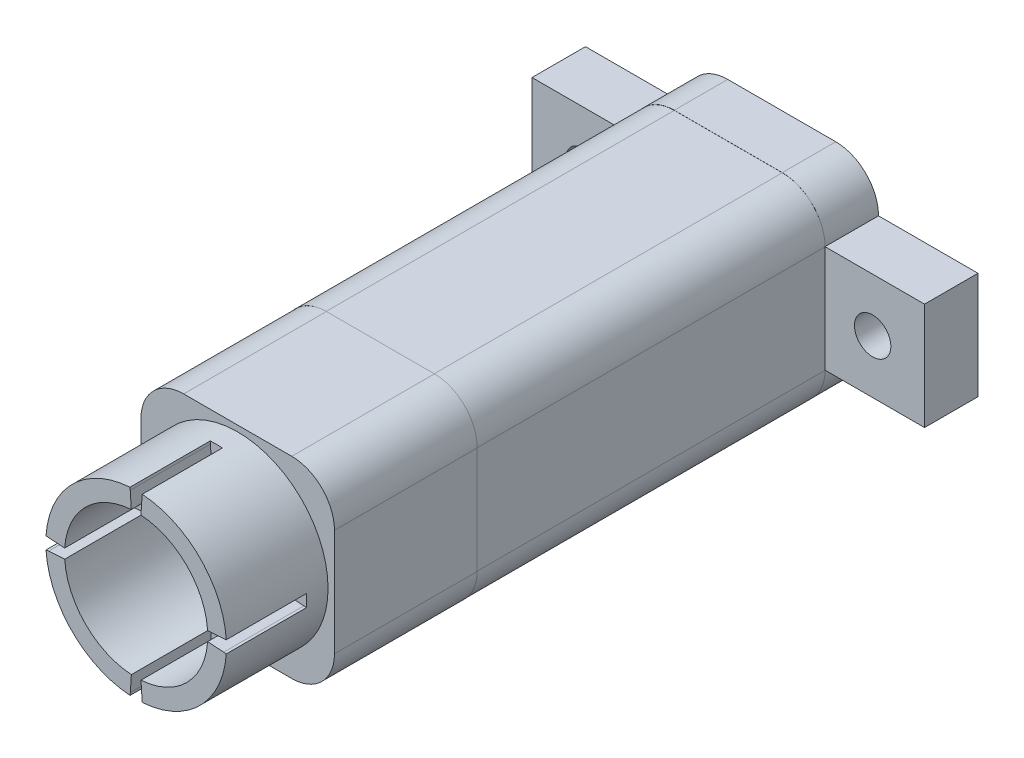
SolidWorks part; units mm, degrees
ref_plane "Front Plane" through (0, 0, 0) normal (0, 0, 1) x (1, 0, 0)
ref_plane "Top Plane" through (0, 0, 0) normal (0, 1, 0) x (1, 0, 0)
ref_plane "Right Plane" through (0, 0, 0) normal (1, 0, 0) x (0, 0, -1)
sketch "Sketch1" plane through (0, 0, 0) normal (0, 0, 1) x (1, 0, 0)
  line L12 (-5.05, 9.0001) -> (5.05, 9.0001)
  line L13 (-9.05, 5.0001) -> (-9.05, -5.0001)
  line L14 (-5.05, -9.0001) -> (5.05, -9.0001)
  line L15 (9.05, 5.0001) -> (9.05, -5.0001)
  line L16 (-9.05, 9.0001) -> (9.05, -9.0001) construction
  line L17 (-9.05, -9.0001) -> (9.05, 9.0001) construction
  arc A4 (-9.05, -5.0001) -> (-5.05, -9.0001) centre (-5.05, -5.0001) ccw
  arc A5 (5.05, -9.0001) -> (9.05, -5.0001) centre (5.05, -5.0001) ccw
  arc A6 (5.05, 9.0001) -> (9.05, 5.0001) centre (5.05, 5.0001) cw
  arc A7 (-5.05, 9.0001) -> (-9.05, 5.0001) centre (-5.05, 5.0001) ccw
  point P0 (0, 0)
  dimension "D2" = 4
  dimension "D1" = 9.05
extrude "Boss-Extrude1" add sketch "Sketch1" along normal blind 2
sketch "Sketch2" plane through (0, 0, 0) normal (0, 0, 1) x (1, 0, 0)
  line L0 (-5.05, 9.0001) -> (5.05, 9.0001)
  line L1 (-9.05, 5.0001) -> (-9.05, -5.0001)
  line L2 (-5.05, -9.0001) -> (5.05, -9.0001)
  line L3 (9.05, 5.0001) -> (9.05, -5.0001)
  line L4 (-9.05, 9.0001) -> (9.05, -9.0001) construction
  line L5 (-9.05, -9.0001) -> (9.05, 9.0001) construction
  arc A0 (-9.05, -5.0001) -> (-5.05, -9.0001) centre (-5.05, -5.0001) ccw
  arc A1 (5.05, -9.0001) -> (9.05, -5.0001) centre (5.05, -5.0001) ccw
  arc A2 (5.05, 9.0001) -> (9.05, 5.0001) centre (5.05, 5.0001) cw
  arc A3 (-5.05, 9.0001) -> (-9.05, 5.0001) centre (-5.05, 5.0001) ccw
  point P0 (0, 0)
  dimension "D2" = 4
  dimension "D1" = 9.05
extrude "Boss-Extrude2" add sketch "Sketch2" along normal blind 11.7499
sketch "Sketch3" plane through (0, 0, 11.7499) normal (0, 0, 1) x (1, 0, 0)
  line L1 (-5.05, 9.0001) -> (5.05, 9.0001)
  line L2 (-9.05, 5.0001) -> (-9.05, -5.0001)
  line L3 (-5.05, -9.0001) -> (5.05, -9.0001)
  line L4 (9.05, 5.0001) -> (9.05, -5.0001)
  line L5 (-9.05, 9.0001) -> (9.05, -9.0001) construction
  line L6 (-9.05, -9.0001) -> (9.05, 9.0001) construction
  arc A0 (-9.05, -5.0001) -> (-5.05, -9.0001) centre (-5.05, -5.0001) ccw
  arc A1 (5.05, -9.0001) -> (9.05, -5.0001) centre (5.05, -5.0001) ccw
  arc A2 (5.05, 9.0001) -> (9.05, 5.0001) centre (5.05, 5.0001) cw
  arc A3 (-5.05, 9.0001) -> (-9.05, 5.0001) centre (-5.05, 5.0001) ccw
  point P0 (0, 0)
  dimension "D2" = 4
  dimension "D1" = 9.05
extrude "Boss-Extrude3" add sketch "Sketch3" along normal blind 1.6
sketch "Sketch4" plane through (0, 0, 13.3499) normal (0, 0, 1) x (1, 0, 0)
  circle A1 centre (0, 0) radius 8.45
  dimension "D2" = 16.9
extrude "Boss-Extrude4" add sketch "Sketch4" along normal blind 9.5
sketch "Sketch5" plane through (0, 0, 13.3499) normal (0, 0, 1) x (1, 0, 0)
  circle A0 centre (0, 0) radius 6.65
  dimension "D1" = 13.3
extrude "Cut-Extrude1" cut sketch "Sketch5" along normal blind 20
sketch "Sketch12" plane through (0, 0, 0) normal (0, 0, -1) x (-1, 0, 0)
  line L0 (-5.0274, 8.9973) -> (5.0726, 8.9973)
  line L1 (-9.0274, 4.9973) -> (-9.0274, -5.0029)
  line L2 (-5.0274, -9.0029) -> (5.0726, -9.0029)
  line L3 (9.0726, 4.9973) -> (9.0726, -5.0029)
  line L4 (-9.0274, 8.9973) -> (9.0726, -9.0029) construction
  line L5 (-9.0274, -9.0029) -> (9.0726, 8.9973) construction
  arc A0 (-9.0274, -5.0029) -> (-5.0274, -9.0029) centre (-5.0274, -5.0029) ccw
  arc A1 (5.0726, -9.0029) -> (9.0726, -5.0029) centre (5.0726, -5.0029) ccw
  arc A2 (5.0726, 8.9973) -> (9.0726, 4.9973) centre (5.0726, 4.9973) cw
  arc A3 (-5.0274, 8.9973) -> (-9.0274, 4.9973) centre (-5.0274, 4.9973) ccw
  point P0 (0.0226, -0.0028)
  dimension "D2" = 4
  dimension "D1" = 9.05
extrude "Boss-Extrude5" add sketch "Sketch12" along normal blind 32.56 contours L0 A2 L3 A1 L2 A0 L1 A3
sketch "Sketch13" plane through (0, 0, 0) normal (0, 0, 1) x (1, 0, 0)
  circle A0 centre (0, 0) radius 6.7
  dimension "D1" = 13.4
extrude "Cut-Extrude3" cut sketch "Sketch13" against normal mid plane 60
sketch "Sketch15" plane through (0, 0, 22.8499) normal (0, 0, 1) x (1, 0, 0)
  line L1 (-0.5528, 8.1871) -> (-0.0028, 0.0033)
  line L3 (0.5472, 8.1871) -> (-0.0028, 0.0033)
  line L4 (-0.5528, 8.1871) -> (-0.626, 9.0001)
  line L5 (5.05, 9.0001) -> (-5.05, 9.0001) construction
  line L6 (-0.626, 9.0001) -> (0.6172, 9.0001)
  line L7 (0.6172, 9.0001) -> (0.5472, 8.1871)
  dimension "D3" = 0.0732
  dimension "D4" = 0.07
extrude "Cut-Extrude4" cut sketch "Sketch15" against normal blind 7.5 contours L1 L3 L7 L6 L4
pattern_circular "CirPattern2" count 4 over 360 about axis through (0, 0, 0) along (0, 0, 1) of "Cut-Extrude4"
sketch "Sketch16" plane through (0, 0, -32.56) normal (0, 0, -1) x (-1, 0, 0)
  line L4 (-5.0234, 9.0084) -> (5.0766, 9.0084)
  line L6 (-5.0234, -8.9918) -> (5.0766, -8.9918)
  line L12 (-9.0234, 9.0084) -> (9.0766, -8.9918) construction
  line L13 (-9.0234, -8.9918) -> (9.0766, 9.0084) construction
  line L14 (0.0266, 0.0083) -> (0.0266, 11.7541) construction
  line L21 (-9.0234, 5.0084) -> (-18.3302, 5.0084)
  line L22 (-18.3302, 5.0084) -> (-18.3302, -4.9918)
  line L23 (-18.3302, -4.9918) -> (-9.0234, -4.9918)
  line L24 (18.3833, -4.9918) -> (9.0766, -4.9918)
  line L25 (18.3833, 5.0084) -> (18.3833, -4.9918)
  line L26 (9.0766, 5.0084) -> (18.3833, 5.0084)
  arc A6 (-9.0234, -4.9918) -> (-5.0234, -8.9918) centre (-5.0234, -4.9918) ccw
  arc A7 (5.0766, -8.9918) -> (9.0766, -4.9918) centre (5.0766, -4.9918) ccw
  arc A8 (5.0766, 9.0084) -> (9.0766, 5.0084) centre (5.0766, 5.0084) cw
  arc A9 (-5.0234, 9.0084) -> (-9.0234, 5.0084) centre (-5.0234, 5.0084) ccw
  circle A10 centre (-13.4772, 0.0083) radius 1.7
  circle A11 centre (13.5304, 0.0083) radius 1.7
  point P0 (0.0266, 0.0083)
  point P17 (0.0266, 0.0083)
  dimension "D2" = 4
  dimension "D3" = 3.4
  dimension "D4" = 13.5038
extrude "Boss-Extrude6" add sketch "Sketch16" along normal blind 5 separate body
